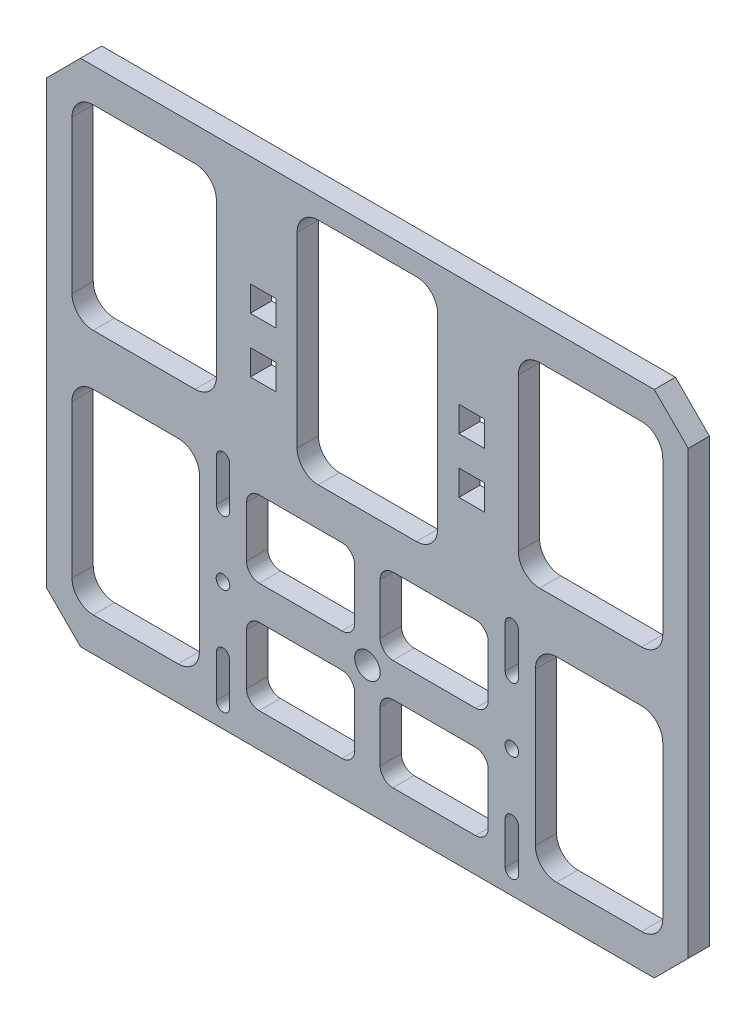
SolidWorks part; units mm, degrees
material "聚亚安酯(11671)"
ref_plane "前视基准面" through (0, 0, 0) normal (0, 0, 1) x (1, 0, 0)
ref_plane "上视基准面" through (0, 0, 0) normal (0, 1, 0) x (1, 0, 0)
ref_plane "右视基准面" through (0, 0, 0) normal (1, 0, 0) x (0, 0, -1)
sketch "草图1" plane through (0, 0, 0) normal (0, 0, 1) x (1, 0, 0)
  line L0 (0, 25.3348) -> (0, -24.5642) construction
  line L1 (-32.3964, 0) -> (31.6755, 0) construction
  line L2 (35.55, -25) -> (32.45, -25)
  line L3 (-75.55, -30) -> (75.55, -30)
  line L4 (-75.55, -30) -> (-75.55, 30)
  line L5 (-75.55, 30) -> (75.55, 30)
  line L6 (75.55, -30) -> (75.55, 30)
  line L7 (-75.55, -30) -> (75.55, 30) construction
  line L8 (-75.55, 30) -> (75.55, -30) construction
  line L9 (-35.55, 25) -> (-32.45, 25)
  line L10 (-35.55, 25) -> (-35.55, 15)
  line L11 (-35.55, 15) -> (-32.45, 15)
  line L12 (-32.45, 25) -> (-32.45, 15)
  line L13 (-35.55, -15) -> (-32.45, -15)
  line L14 (-35.55, -15) -> (-35.55, -25)
  line L15 (-35.55, -25) -> (-32.45, -25)
  line L16 (-32.45, -15) -> (-32.45, -25)
  line L17 (32.45, -15) -> (32.45, -25)
  line L18 (35.55, -15) -> (32.45, -15)
  line L19 (35.55, -15) -> (35.55, -25)
  line L20 (35.55, 15) -> (32.45, 15)
  line L21 (32.45, 25) -> (32.45, 15)
  line L22 (35.55, 25) -> (32.45, 25)
  line L23 (35.55, 25) -> (35.55, 15)
  line L24 (34, -15) -> (34, 15) construction
  circle A0 centre (0, 0) radius 3
  circle A1 centre (34, 0) radius 1.6
  circle A2 centre (-34, 0) radius 1.6
  point P5 (0, 0)
  point P22 (-32.45, -20)
  point P23 (-32.45, 20)
  point P25 (-34, 15)
  dimension "D7" = 6
  dimension "D8" = 3.2
  dimension "D1" = 40
  dimension "D2" = 3.1
  dimension "D3" = 10
  dimension "D4" = 40
  dimension "D5" = 68
  dimension "D6" = 5
extrude "凸台-拉伸1" add sketch "草图1" along normal blind 5
sketch "草图2" plane through (0, 0, 5) normal (0, 0, 1) x (1, 0, 0)
  line L0 (-32.45, 25) -> (-35.55, 25) construction
  line L1 (-35.55, 15) -> (-32.45, 15) construction
  line L2 (35.55, 25) -> (32.45, 25) construction
  line L3 (32.45, 15) -> (35.55, 15) construction
  line L4 (35.55, -15) -> (32.45, -15) construction
  line L5 (32.45, -25) -> (35.55, -25) construction
  line L6 (-32.45, -15) -> (-35.55, -15) construction
  line L7 (-35.55, -25) -> (-32.45, -25) construction
  line L8 (0, 30) -> (0, -30) construction
  line L9 (75.55, 30) -> (-75.55, 30) construction
  line L10 (-75.55, -30) -> (75.55, -30) construction
  line L11 (-75.55, 0) -> (75.55, 0) construction
  line L12 (-75.55, 30) -> (-75.55, -30) construction
  line L13 (75.55, -30) -> (75.55, 30) construction
  line L14 (-32.45, -25) -> (-32.45, -15) construction
  line L15 (-28.45, 22) -> (-3, 22)
  line L16 (-28.45, 22) -> (-28.45, 4)
  line L17 (-28.45, 4) -> (-3, 4)
  line L18 (28.45, 22) -> (28.45, 4)
  line L19 (-28.45, 22) -> (28.45, 4) construction
  line L20 (-28.45, 4) -> (28.45, 22) construction
  line L21 (-28.45, -4) -> (-3, -4)
  line L22 (-28.45, -4) -> (-28.45, -22)
  line L23 (-28.45, -22) -> (-3, -22)
  line L24 (28.45, -4) -> (28.45, -22)
  line L25 (-28.45, -4) -> (28.45, -22) construction
  line L26 (-28.45, -22) -> (28.45, -4) construction
  line L27 (-3, 22) -> (-3, 4)
  line L28 (3, 22) -> (3, 4)
  line L29 (-3, -4) -> (-3, -22)
  line L30 (3, -4) -> (3, -22)
  line L31 (3, 22) -> (28.45, 22)
  line L32 (3, 4) -> (28.45, 4)
  line L33 (3, -4) -> (28.45, -4)
  line L34 (3, -22) -> (28.45, -22)
  circle A0 centre (-34, 25) radius 1.55
  circle A1 centre (-34, 15) radius 1.55
  circle A2 centre (34, 25) radius 1.55
  circle A3 centre (34, 15) radius 1.55
  circle A4 centre (34, -15) radius 1.55
  circle A5 centre (34, -25) radius 1.55
  circle A6 centre (-34, -15) radius 1.55
  circle A7 centre (-34, -25) radius 1.55
  circle A8 centre (0, 0) radius 3 construction
  point P52 (0, 13)
  point P57 (0, -13)
  dimension "D1" = 4
  dimension "D2" = 8
  dimension "D3" = 4
  dimension "D4" = 6
extrude "切除-拉伸1" cut sketch "草图2" against normal through all
fillet "圆角1" radius 3 16 edges at (-28.45, -22, 2.5) (-28.45, -4, 2.5) (-28.45, 4, 2.5) (-28.45, 22, 2.5) (3, 4, 2.5) (3, 22, 2.5) (-3, 22, 2.5) (-3, 4, 2.5) (-3, -22, 2.5) (-3, -4, 2.5) (3, -22, 2.5) (3, -4, 2.5) (28.45, -4, 2.5) (28.45, -22, 2.5) (28.45, 4, 2.5) (28.45, 22, 2.5)
sketch "草图3" plane through (0, 0, 5) normal (0, 0, 1) x (1, 0, 0)
  line L0 (75.55, -30) -> (75.55, 30) construction
  line L1 (-75.55, 90) -> (75.55, 90)
  line L2 (-75.55, 90) -> (-75.55, 30)
  line L3 (-75.55, 30) -> (75.55, 30)
  line L4 (75.55, 90) -> (75.55, 30)
  line L5 (0, 0) -> (0, 90) construction
  line L6 (27.55, 45) -> (21.55, 45)
  line L7 (-27.55, 64) -> (-21.55, 64)
  line L8 (-27.55, 64) -> (-27.55, 58)
  line L9 (-27.55, 58) -> (-21.55, 58)
  line L10 (-21.55, 64) -> (-21.55, 58)
  line L11 (-27.55, 51) -> (-21.55, 51)
  line L12 (-27.55, 51) -> (-27.55, 45)
  line L13 (-27.55, 45) -> (-21.55, 45)
  line L14 (-21.55, 51) -> (-21.55, 45)
  line L19 (21.55, 51) -> (21.55, 45)
  line L20 (27.55, 51) -> (21.55, 51)
  line L21 (27.55, 51) -> (27.55, 45)
  line L22 (27.55, 58) -> (21.55, 58)
  line L23 (21.55, 64) -> (21.55, 58)
  line L24 (27.55, 64) -> (21.55, 64)
  line L25 (27.55, 64) -> (27.55, 58)
  line L27 (-16.55, 85) -> (16.55, 85)
  line L28 (-16.55, 85) -> (-16.55, 31)
  line L29 (-16.55, 31) -> (16.55, 31)
  line L30 (16.55, 85) -> (16.55, 31)
  dimension "D1" = 60
  dimension "D2" = 48
  dimension "D3" = 54
  dimension "D4" = 6
  dimension "D5" = 13
  dimension "D6" = 15
  dimension "D7" = 5
  dimension "D8" = 1
  dimension "D9" = 5
  dimension "D10" = 43.1
  dimension "D11" = 55.1
extrude "凸台-拉伸2" add sketch "草图3" against normal up to surface (5 mm away) up to face at (34, -20, 0)
sketch "草图4" plane through (0, 0, 5) normal (0, 0, 1) x (1, 0, 0)
  line L1 (-69.55, 82) -> (-35.55, 82)
  line L2 (-69.55, 82) -> (-69.55, 36)
  line L3 (-69.55, 36) -> (-35.55, 36)
  line L4 (-35.55, 82) -> (-35.55, 36)
  line L5 (-69.55, 24) -> (-39.55, 24)
  line L6 (-69.55, 24) -> (-69.55, -22)
  line L7 (-69.55, -22) -> (-39.55, -22)
  line L8 (-39.55, 24) -> (-39.55, -22)
  line L17 (0, 90) -> (0, 0) construction
  line L18 (75.55, 90) -> (-75.55, 90) construction
  line L19 (-75.55, 30) -> (75.55, 30) construction
  line L20 (-75.55, 90) -> (-75.55, -30) construction
  line L21 (75.55, -30) -> (75.55, 90) construction
  line L22 (-35.55, 25) -> (-35.55, 15) construction
  line L23 (-27.55, 64) -> (-27.55, 58) construction
  line L24 (69.55, -22) -> (39.55, -22)
  line L25 (39.55, 24) -> (39.55, -22)
  line L26 (69.55, 24) -> (39.55, 24)
  line L27 (69.55, 24) -> (69.55, -22)
  line L28 (69.55, 36) -> (35.55, 36)
  line L29 (35.55, 82) -> (35.55, 36)
  line L30 (69.55, 82) -> (35.55, 82)
  line L31 (69.55, 82) -> (69.55, 36)
  dimension "D1" = 6
  dimension "D2" = 4
  dimension "D3" = 8
  dimension "D4" = 6
  dimension "D5" = 6
  dimension "D6" = 8
extrude "切除-拉伸2" cut sketch "草图4" against normal through all
fillet "圆角2" radius 5 20 edges at (69.55, 24, 2.5) (69.55, -22, 2.5) (39.55, -22, 2.5) (39.55, 24, 2.5) (69.55, 36, 2.5) (69.55, 82, 2.5) (35.55, 82, 2.5) (35.55, 36, 2.5) (16.55, 31, 2.5) (16.55, 85, 2.5) (-16.55, 85, 2.5) (-16.55, 31, 2.5) (-39.55, -22, 2.5) (-69.55, -22, 2.5) (-39.55, 24, 2.5) (-69.55, 24, 2.5) (-69.55, 36, 2.5) (-69.55, 82, 2.5) (-35.55, 82, 2.5) (-35.55, 36, 2.5)
chamfer "倒角1" distance 8 angle 45 4 edges at (-75.55, -30, 2.5) (75.55, -30, 2.5) (75.55, 90, 2.5) (-75.55, 90, 2.5)
